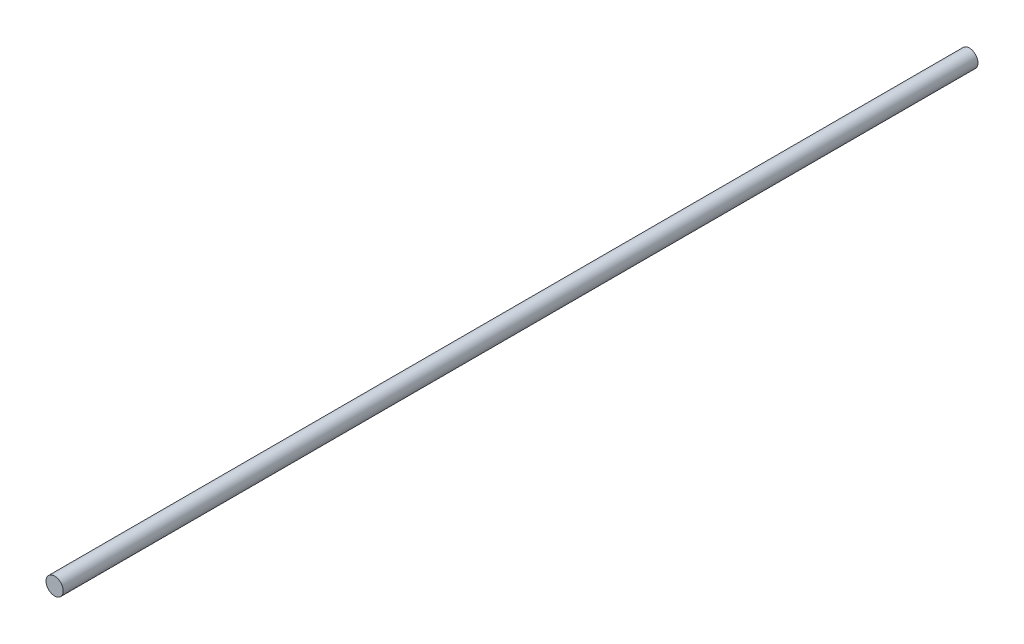
SolidWorks part; units mm, degrees
material "镀铬光轴"
ref_plane "前视" through (0, 0, 0) normal (0, 0, 1) x (1, 0, 0)
ref_plane "上视" through (0, 0, 0) normal (0, 1, 0) x (1, 0, 0)
ref_plane "右视" through (0, 0, 0) normal (1, 0, 0) x (0, 0, -1)
sketch "草图1" plane through (0, 0, 0) normal (0, 0, 1) x (1, 0, 0)
  circle A0 centre (0, 0) radius 10
  dimension "D1" = 20
extrude "凸台-拉伸1" add sketch "草图1" along normal mid plane 1060
